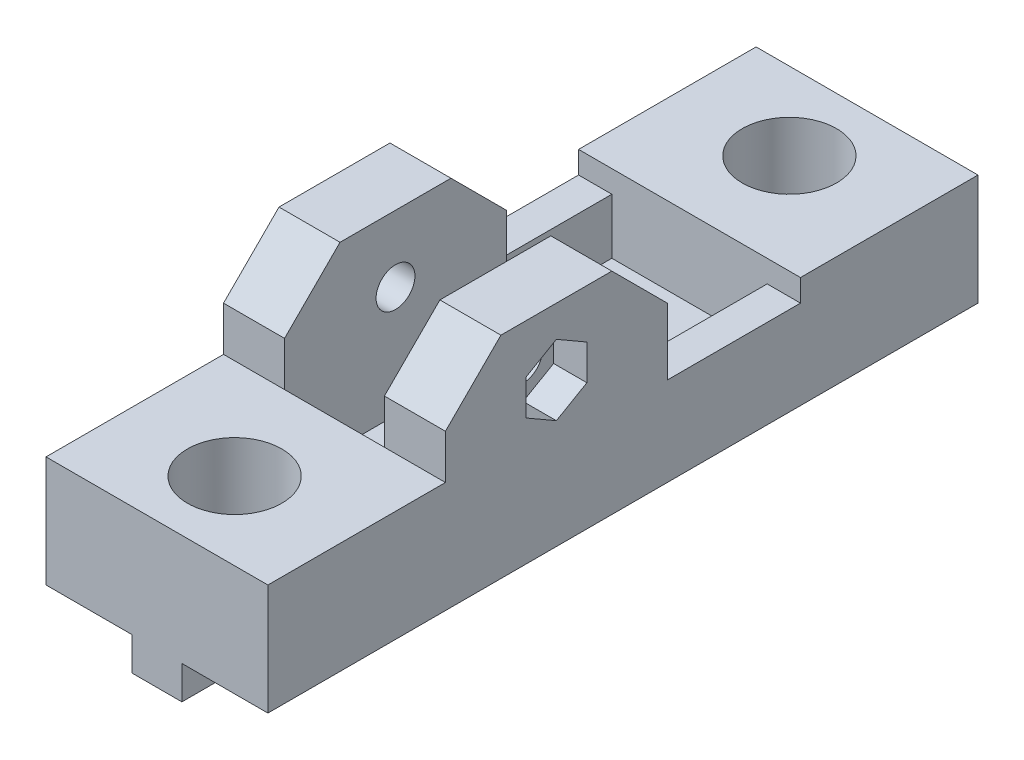
SolidWorks part; units mm, degrees
ref_plane "Front Plane" through (0, 0, 0) normal (0, 0, 1) x (1, 0, 0)
ref_plane "Top Plane" through (0, 0, 0) normal (0, 1, 0) x (1, 0, 0)
ref_plane "Right Plane" through (0, 0, 0) normal (1, 0, 0) x (0, 0, -1)
sketch "Sketch1" plane through (0, 0, 0) normal (0, 1, 0) x (1, 0, 0)
  line L1 (-10, -15) -> (10, -15)
  line L2 (-10, -15) -> (-10, 15)
  line L3 (-10, 15) -> (10, 15)
  line L4 (10, -15) -> (10, 15)
  line L5 (-10, -15) -> (10, 15) construction
  line L6 (-10, 15) -> (10, -15) construction
  point P0 (0, 0)
  dimension "D1" = 20
  dimension "D2" = 30
extrude "Boss-Extrude1" add sketch "Sketch1" along normal blind 3
sketch "Sketch2" plane through (0, 0, 0) normal (0, -1, 0) x (1, 0, 0)
  line L0 (10, -15) -> (-10, -15) construction
  line L1 (-2.25, -15) -> (2.25, -15)
  line L2 (-2.25, -15) -> (-2.25, -3)
  line L3 (-2.25, -3) -> (2.25, -3)
  line L4 (2.25, -15) -> (2.25, -3)
  line L5 (-2.25, -15) -> (2.25, -3) construction
  line L6 (-2.25, -3) -> (2.25, -15) construction
  point P0 (0, -9)
  dimension "D1" = 0
  dimension "D2" = 4.5
  dimension "D3" = 0
  dimension "D4" = 12
extrude "Boss-Extrude2" add sketch "Sketch2" along normal blind 3
sketch "Sketch3" plane through (0, 3, 0) normal (0, 1, 0) x (1, 0, 0)
  line L0 (10, 15) -> (-10, 15) construction
  circle A0 centre (0, 8) radius 4.25
  circle A1 centre (0, 8) radius 7
  dimension "D1" = 14
  dimension "D2" = 7
  dimension "D3" = 8.5
extrude "Boss-Extrude3" add sketch "Sketch3" along normal blind 7
sketch "Sketch4" plane through (0, 3, 0) normal (0, 1, 0) x (1, 0, 0)
  circle A1 centre (0, 8) radius 4.25
  circle A2 centre (0, 8) radius 4.25
  dimension "D1" = 0
extrude "Boss-Extrude4" add sketch "Sketch4" along normal blind 1
sketch "Sketch5" plane through (0, 3, 0) normal (0, 1, 0) x (1, 0, 0)
  line L0 (-10, -15) -> (10, -15) construction
  circle A0 centre (0, -8.5) radius 3
  point P4 (0, 0)
  point P7 (-0.7919, -3)
  dimension "D1" = 6
  dimension "D2" = 6.5
  dimension "D3" = 0
extrude "Cut-Extrude1" cut sketch "Sketch5" against normal through all both and the other way through all
chamfer "Chamfer1" [suppressed] distance 4 angle 45
sketch "Sketch6" plane through (0, 3, 0) normal (0, 1, 0) x (1, 0, 0)
  line L0 (10, -15) -> (10, 15) construction
  line L1 (-10, 15) -> (10, 15)
  line L2 (-10, 15) -> (-10, -1)
  line L3 (-10, -1) -> (10, -1)
  line L4 (10, 15) -> (10, -1)
  circle A0 centre (0, 8) radius 7 construction
  circle A1 centre (0, 8) radius 7
  circle A3 centre (0, 8) radius 4.25
  circle A4 centre (0, 8) radius 4.25
  line M6 (10, 15) -> (0, 15)
  circle M7 centre (0, 8) radius 7
  line M8 (0, 15) -> (-10, 15)
  line M9 (-10, 15) -> (-10, -15)
  line M11 (10, -15) -> (10, 15)
  dimension "D1" = 16
  dimension "D2" = 0
extrude "Boss-Extrude6" add sketch "Sketch6" along normal up to surface (7 mm away) contours A4 M7 | L3 M9 M11 M6 M7 M8 up to face at (0, 10, -1)
ref_plane "Plane1" through (0, 0, -8) normal (0, 0, 1) x (1, 0, 0)
ref_plane "Plane2" through (0, 0, 17) normal (0, 0, 1) x (1, 0, 0)
sketch "Sketch7" plane through (0, 0, 15) normal (0, 0, 1) x (1, 0, 0)
  line L4 (-10, 0) -> (10, 0)
  line L5 (10, 0) -> (10, 3)
  line L6 (10, 3) -> (-10, 3)
  line L7 (-10, 3) -> (-10, 0)
  line L8 (-10, 0) -> (10, 0)
  line L9 (10, 0) -> (10, 3)
  line L10 (10, 3) -> (-10, 3)
  line L11 (-10, 3) -> (-10, 0)
  dimension "D1" = 0
extrude "Boss-Extrude7" add sketch "Sketch7" along normal blind 19
mirror "Mirror3" about plane through (0, 0, 17) normal (0, 0, 1) of "Boss-Extrude6", "Boss-Extrude4", "Boss-Extrude3", "Boss-Extrude2", "Boss-Extrude1"
sketch "Sketch8" plane through (0, 0, 37) normal (0, 0, -1) x (-1, 0, 0)
  line L4 (2.25, 0) -> (-2.25, 0)
  line L5 (-2.25, 0) -> (-2.25, -3)
  line L6 (-2.25, -3) -> (2.25, -3)
  line L7 (2.25, -3) -> (2.25, 0)
  line L8 (2.25, 0) -> (-2.25, 0)
  line L9 (-2.25, 0) -> (-2.25, -3)
  line L10 (-2.25, -3) -> (2.25, -3)
  line L11 (2.25, -3) -> (2.25, 0)
  dimension "D1" = 0
extrude "Boss-Extrude8" add sketch "Sketch8" along normal blind 12
sketch "Sketch10" plane through (0, 3, 0) normal (0, 1, 0) x (1, 0, 0)
  line L0 (-10, -33) -> (10, -33) construction
  line L1 (4.5, -13) -> (-4.5, -13)
  line L2 (4.5, -13) -> (4.5, -33)
  line L3 (4.5, -33) -> (-4.5, -33)
  line L4 (-4.5, -13) -> (-4.5, -33)
  line L5 (4.5, -13) -> (-4.5, -33) construction
  line L6 (4.5, -33) -> (-4.5, -13) construction
  line L8 (-10, -1) -> (-10, -33) construction
  line L9 (-4.5, -13) -> (-10, -13)
  line L10 (-4.5, -13) -> (-4.5, -33)
  line L11 (-4.5, -33) -> (-10, -33)
  line L12 (-10, -13) -> (-10, -33)
  line L14 (4.5, -13) -> (10, -13)
  line L15 (4.5, -13) -> (4.5, -33)
  line L16 (4.5, -33) -> (10, -33)
  line L17 (10, -13) -> (10, -33)
  circle A0 centre (0, -8.5) radius 3 construction
  circle A1 centre (0, -8.5) radius 3
  circle A2 centre (0, -8.5) radius 6
  point P0 (0, -23)
  line M15 (-10, -1) -> (-10, -33)
  line M16 (-10, -33) -> (10, -33)
  line M17 (10, -33) -> (10, -1)
  dimension "D4" = 12
  dimension "D1" = 0
  dimension "D2" = 20
  dimension "D3" = 9
extrude "Boss-Extrude9" add sketch "Sketch10" along normal blind 16 contours L4 L9 M15 M16 | L14 L2 M16 M17
sketch "Sketch11" plane through (-10, 0, 0) normal (-1, 0, 0) x (0, 0, 1)
  line L0 (17, -11) -> (17, 11) construction
  circle A0 centre (23, 13) radius 1.75
  dimension "D3" = 3.5
  dimension "D1" = 6
  dimension "D2" = 10
extrude "Cut-Extrude2" cut sketch "Sketch11" against normal through all both and the other way through all
sketch "Sketch12" plane through (-10, 0, 0) normal (-1, 0, 0) x (0, 0, 1)
  circle A0 centre (23, 13) radius 1.75 construction
  circle A1 centre (23, 13) radius 1.75
  circle A2 centre (23, 13) radius 3
  dimension "D1" = 6
extrude "Cut-Extrude3" cut sketch "Sketch12" against normal blind 3
sketch "Sketch13" plane through (10, 0, 0) normal (1, 0, 0) x (0, 0, -1)
  line L1 (-23, 16.1754) -> (-25.75, 14.5877)
  line L2 (-25.75, 14.5877) -> (-25.75, 11.4123)
  line L3 (-25.75, 11.4123) -> (-23, 9.8246)
  line L4 (-23, 9.8246) -> (-20.25, 11.4123)
  line L5 (-20.25, 11.4123) -> (-20.25, 14.5877)
  line L6 (-20.25, 14.5877) -> (-23, 16.1754)
  circle A0 centre (-23, 13) radius 1.75 construction
  circle A1 centre (-23, 13) radius 1.75
  circle A2 centre (-23, 13) radius 2.75 construction
  dimension "D1" = 5.5
extrude "Cut-Extrude4" cut sketch "Sketch13" against normal blind 3
chamfer "Chamfer2" distance 5 angle 45 4 edges at (7.25, 19, 13) (7.25, 19, 33) (-7.25, 19, 33) (-7.25, 19, 13)
sketch "Sketch14" plane through (0, 4, 0) normal (0, 1, 0) x (1, 0, 0)
  circle A0 centre (0, -42) radius 4.25 construction
  circle A1 centre (0, 8) radius 4.25 construction
  circle A2 centre (0, -42) radius 4.25
  circle A3 centre (0, 8) radius 4.25
extrude "Cut-Extrude5" cut sketch "Sketch14" against normal blind 1.5
sketch "Sketch15" plane through (0, 3, 0) normal (0, 1, 0) x (1, 0, 0)
  line L1 (-10, -1) -> (-7, -1)
  line L2 (-10, -1) -> (-10, -13)
  line L3 (-10, -13) -> (-7, -13)
  line L4 (-7, -1) -> (-7, -13)
  line L5 (10, -1) -> (7, -1)
  line L6 (10, -1) -> (10, -13)
  line L7 (10, -13) -> (7, -13)
  line L8 (4.5, -33) -> (4.5, -13)
  line L9 (4.5, -13) -> (10, -13)
  line L10 (10, -13) -> (10, -1)
  line L11 (10, -1) -> (-10, -1)
  line L12 (-10, -1) -> (-10, -13)
  line L13 (-10, -13) -> (-4.5, -13)
  line L14 (-4.5, -13) -> (-4.5, -33)
  line L15 (-4.5, -33) -> (4.5, -33)
  line L16 (4.5, -33) -> (4.5, -13)
  line L17 (4.5, -13) -> (10, -13)
  line L18 (10, -13) -> (10, -1)
  line L19 (10, -1) -> (-10, -1)
  line L20 (-10, -1) -> (-10, -13)
  line L21 (-10, -13) -> (-4.5, -13)
  line L22 (-4.5, -13) -> (-4.5, -33)
  line L23 (-4.5, -33) -> (4.5, -33)
  line L24 (7, -1) -> (7, -13)
  line M15 (4.5, -13) -> (10, -13)
  line M16 (10, -13) -> (10, -1)
  line M17 (10, -1) -> (-10, -1)
  line M18 (-10, -1) -> (-10, -13)
  line M19 (-10, -13) -> (-4.5, -13)
  dimension "D2" = 3
  dimension "D3" = 3
  dimension "D1" = 0
extrude "Boss-Extrude10" add sketch "Sketch15" along normal blind 5 contours L4 M17 M18 M19 | L24 M17 M15 M16
